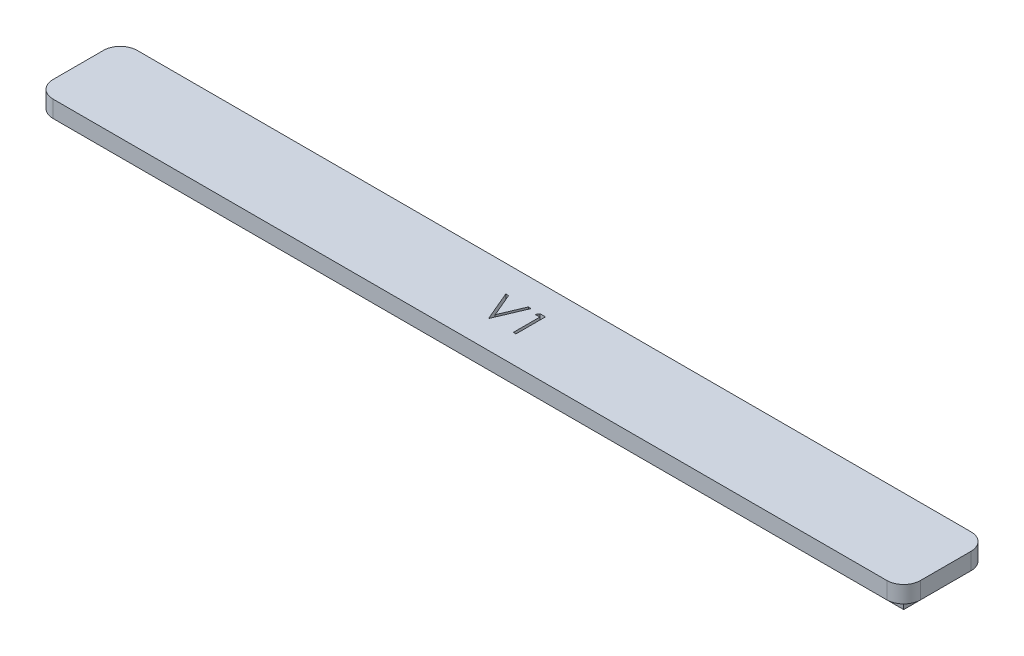
SolidWorks part; units mm, degrees
ref_plane "Front Plane" through (0, 0, 0) normal (0, 0, 1) x (1, 0, 0)
ref_plane "Top Plane" through (0, 0, 0) normal (0, 1, 0) x (1, 0, 0)
ref_plane "Right Plane" through (0, 0, 0) normal (1, 0, 0) x (0, 0, -1)
sketch "Sketch1" plane through (0, 0, 0) normal (0, 1, 0) x (1, 0, 0)
  line L1 (-49.5, 3) -> (49.5, 3)
  line L2 (-49.5, 3) -> (-49.5, -3)
  line L3 (-49.5, -3) -> (49.5, -3)
  line L4 (49.5, 3) -> (49.5, -3)
  line L5 (-49.5, 3) -> (49.5, -3) construction
  line L6 (-49.5, -3) -> (49.5, 3) construction
  point P0 (0, 0)
  dimension "D1" = 99
  dimension "D2" = 6
extrude "Boss-Extrude1" add sketch "Sketch1" along normal blind 2
sketch "Sketch2" plane through (0, 2, 0) normal (0, 1, 0) x (1, 0, 0)
  line L0 (50.5, -4) -> (50.5, 4)
  line L1 (50.5, 4) -> (-50.5, 4)
  line L2 (-50.5, 4) -> (-50.5, -4)
  line L3 (-50.5, -4) -> (50.5, -4)
  line L4 (49.5, -3) -> (49.5, 3)
  line L5 (49.5, 3) -> (-49.5, 3)
  line L6 (-49.5, 3) -> (-49.5, -3)
  line L7 (-49.5, -3) -> (49.5, -3)
  line L8 (49.5, -3) -> (49.5, 3) construction
  line L9 (49.5, 3) -> (-49.5, 3) construction
  line L10 (-49.5, 3) -> (-49.5, -3) construction
  line L11 (-49.5, -3) -> (49.5, -3) construction
  dimension "D1" = 0
  dimension "D2" = 1
extrude "Boss-Extrude3" add sketch "Sketch2" along normal blind 2 separate body
draft "Draft1" type of draft neutral plane draft angle 10 faces to draft 4 face at (49.5, 1, 0) face at (0, 1, 3) face at (-49.5, 1, 0) face at (0, 1, -3) neutral plane through (0, 0, 0) neutral plane normal (0, -1, 0) parameters "D1"=10
sketch "Sketch3" plane through (0, 4, 0) normal (0, 1, 0) x (1, 0, 0)
  line L0 (-51.5, -5) -> (51.5, -5)
  line L1 (51.5, -5) -> (51.5, 5)
  line L2 (51.5, 5) -> (-51.5, 5)
  line L3 (-51.5, 5) -> (-51.5, -5)
  line L4 (-50.5, -4) -> (50.5, -4)
  line L5 (50.5, -4) -> (50.5, 4)
  line L6 (50.5, 4) -> (-50.5, 4)
  line L7 (-50.5, 4) -> (-50.5, -4)
  line L8 (-50.5, -4) -> (50.5, -4)
  line L9 (50.5, -4) -> (50.5, 4)
  line L10 (50.5, 4) -> (-50.5, 4)
  line L11 (-50.5, 4) -> (-50.5, -4)
  dimension "D1" = 0
  dimension "D2" = 1
extrude "Boss-Extrude4" add sketch "Sketch3" against normal blind 2
fillet "Fillet1" radius 2 4 edges at (-51.5, 3, -5) (51.5, 3, -5) (51.5, 3, 5) (-51.5, 3, 5)
sketch "Sketch4" plane through (0, 4, 0) normal (0, 1, 0) x (1, 0, 0)
  text T0 "V1"
extrude "Cut-Extrude1" cut sketch "Sketch4" against normal blind 1
